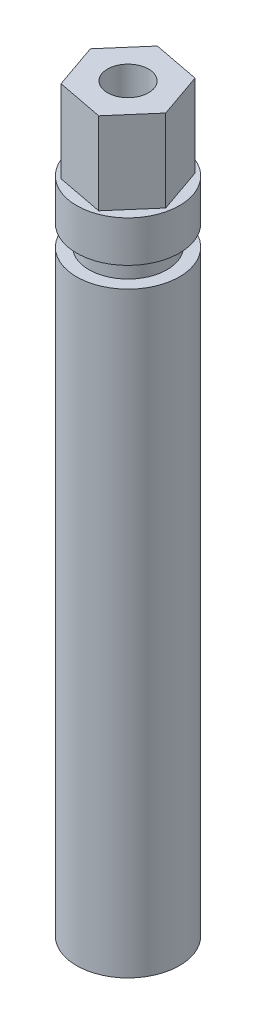
SolidWorks part; units mm, degrees
ref_plane "Front Plane" through (0, 0, 0) normal (0, 0, 1) x (1, 0, 0)
ref_plane "Top Plane" through (0, 0, 0) normal (0, 1, 0) x (1, 0, 0)
ref_plane "Right Plane" through (0, 0, 0) normal (1, 0, 0) x (0, 0, -1)
sketch "Sketch1" plane through (0, 0, 0) normal (0, 1, 0) x (1, 0, 0)
  circle A0 centre (0, 0) radius 6.35
  circle A1 centre (0, 0) radius 15.875
  dimension "D1" = 12.7
  dimension "D2" = 31.75
extrude "Boss-Extrude1" add sketch "Sketch1" along normal blind 215.9
sketch "Sketch2" plane through (0, 0, 0) normal (0, -1, 0) x (1, 0, 0)
  circle A0 centre (0, 0) radius 12.7
  circle A1 centre (0, 0) radius 15.875 construction
  circle A2 centre (0, 0) radius 15.875
  dimension "D1" = 25.4
extrude "Boss-Extrude2" add sketch "Sketch2" along normal blind 12.7
sketch "Sketch3" plane through (0, 0, 0) normal (1, 0, 0) x (0, 0, -1)
  line L0 (15.875, -12.7) -> (15.875, 215.9) construction
  line L1 (15.875, 177.8) -> (12.065, 177.8)
  line L2 (15.875, 177.8) -> (15.875, 171.45)
  line L3 (15.875, 171.45) -> (12.065, 171.45)
  line L4 (12.065, 177.8) -> (12.065, 171.45)
  line L5 (15.875, 215.9) -> (-15.875, 215.9) construction
  line L6 (0, -12.7) -> (0, 215.9) construction
  line L7 (-15.875, -12.7) -> (15.875, -12.7) construction
  dimension "D1" = 38.1
  dimension "D2" = 3.81
  dimension "D3" = 6.35
revolve "Cut-Revolve1" cut sketch "Sketch3" angle 360 about L6
sketch "Sketch4" plane through (0, 215.9, 0) normal (0, 1, 0) x (1, 0, 0)
  line L1 (9.5924, 11.0923) -> (-4.81, 13.8534)
  line L2 (-4.81, 13.8534) -> (-14.4024, 2.7611)
  line L3 (-14.4024, 2.7611) -> (-9.5924, -11.0923)
  line L4 (-9.5924, -11.0923) -> (4.81, -13.8534)
  line L5 (4.81, -13.8534) -> (14.4024, -2.7611)
  line L6 (14.4024, -2.7611) -> (9.5924, 11.0923)
  circle A0 centre (0, 0) radius 12.7 construction
  circle A1 centre (0, 0) radius 15.875 construction
  circle A2 centre (0, 0) radius 15.875
  dimension "D1" = 25.4
extrude "Cut-Extrude1" cut sketch "Sketch4" against normal blind 25.4
